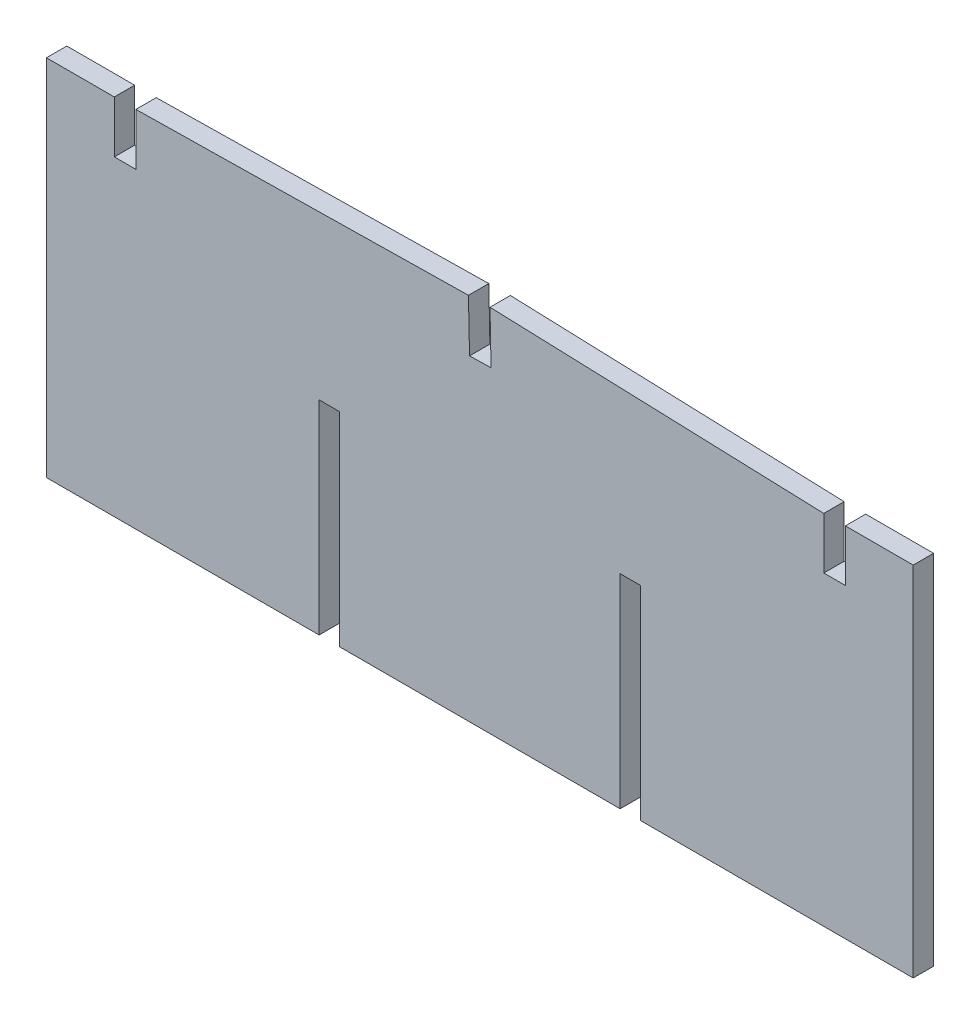
SolidWorks part; units mm, degrees
ref_plane "Front Plane" through (0, 0, 0) normal (0, 0, 1) x (1, 0, 0)
ref_plane "Top Plane" through (0, 0, 0) normal (0, 1, 0) x (1, 0, 0)
ref_plane "Right Plane" through (0, 0, 0) normal (1, 0, 0) x (0, 0, -1)
ref_plane "Plane1" through (0, 0, -353) normal (0, 0, 1) x (1, 0, 0)
sketch "Sketch2" plane through (0, 0, -353) normal (0, 0, 1) x (1, 0, 0)
  line L0 (374.396, 61.5215) -> (374.396, 69.125)
  line L1 (371.221, 61.5215) -> (371.221, 69.1249)
  line L2 (371.221, 61.5215) -> (374.396, 61.5215)
  line L3 (374.396, 69.125) -> (371.221, 69.1249)
  line L6 (371.221, 61.5215) -> (371.221, 69.1249)
  line L7 (374.396, 61.5215) -> (374.396, 69.125)
  line L8 (266.7, 69.9993) -> (266.7, 62.3492)
  line L9 (269.875, 69.9993) -> (269.875, 62.3492)
  line L10 (266.7, 62.3492) -> (269.875, 62.3492)
  line L11 (344.221, 46.4388) -> (344.221, 16.4388) construction
  line L13 (266.7, 62.3492) -> (269.875, 62.3492)
  line L14 (269.875, 69.9993) -> (269.875, 62.3492)
  line L15 (266.7, 69.9993) -> (266.7, 62.3492)
  line L16 (322.0469, 70.8456) -> (322.2054, 63.1957)
  line L17 (318.8725, 70.7799) -> (319.0311, 63.1301)
  line L18 (319.0311, 63.1301) -> (322.2054, 63.1957)
  line L19 (341.221, 46.4388) -> (344.221, 46.4388) construction
  line L21 (319.0311, 63.1301) -> (322.2054, 63.1957)
  line L22 (318.8725, 70.7799) -> (319.0311, 63.1301)
  line L23 (322.0469, 70.8456) -> (322.2054, 63.1957)
  line L24 (374.396, 69.125) -> (384.396, 69.125)
  line L25 (384.396, 69.125) -> (384.396, 16.4388)
  line L26 (371.221, 61.5215) -> (374.396, 61.5215)
  line L27 (384.396, 16.4388) -> (344.221, 16.4388)
  line L28 (266.7, 69.9993) -> (269.875, 69.9993)
  line L29 (322.0469, 70.8456) -> (318.8725, 70.7799)
  line L30 (256.7, 16.4388) -> (256.7, 69.9993)
  line L31 (256.7, 69.9993) -> (266.7, 69.9993)
  line L32 (269.875, 69.9993) -> (318.8725, 70.7799)
  line L33 (322.0469, 70.8456) -> (371.221, 69.1249)
  line L34 (341.221, 16.4388) -> (341.221, 46.4388) construction
  line L35 (299.875, 46.4388) -> (299.875, 16.4388) construction
  line L36 (296.875, 16.4388) -> (296.875, 46.4388) construction
  line L37 (296.875, 46.4388) -> (299.875, 46.4388) construction
  line L38 (344.221, 46.4388) -> (344.221, 16.4388)
  line L39 (341.221, 46.4388) -> (344.221, 46.4388)
  line L40 (341.221, 16.4388) -> (341.221, 46.4388)
  line L41 (299.875, 46.4388) -> (299.875, 16.4388)
  line L42 (296.875, 16.4388) -> (296.875, 46.4388)
  line L43 (296.875, 46.4388) -> (299.875, 46.4388)
  line L44 (296.875, 16.4388) -> (256.7, 16.4388)
  line L45 (341.221, 16.4388) -> (299.875, 16.4388)
  dimension "D1" = 10
  dimension "D2" = 10
extrude "Boss-Extrude1" add sketch "Sketch2" against normal blind 3
